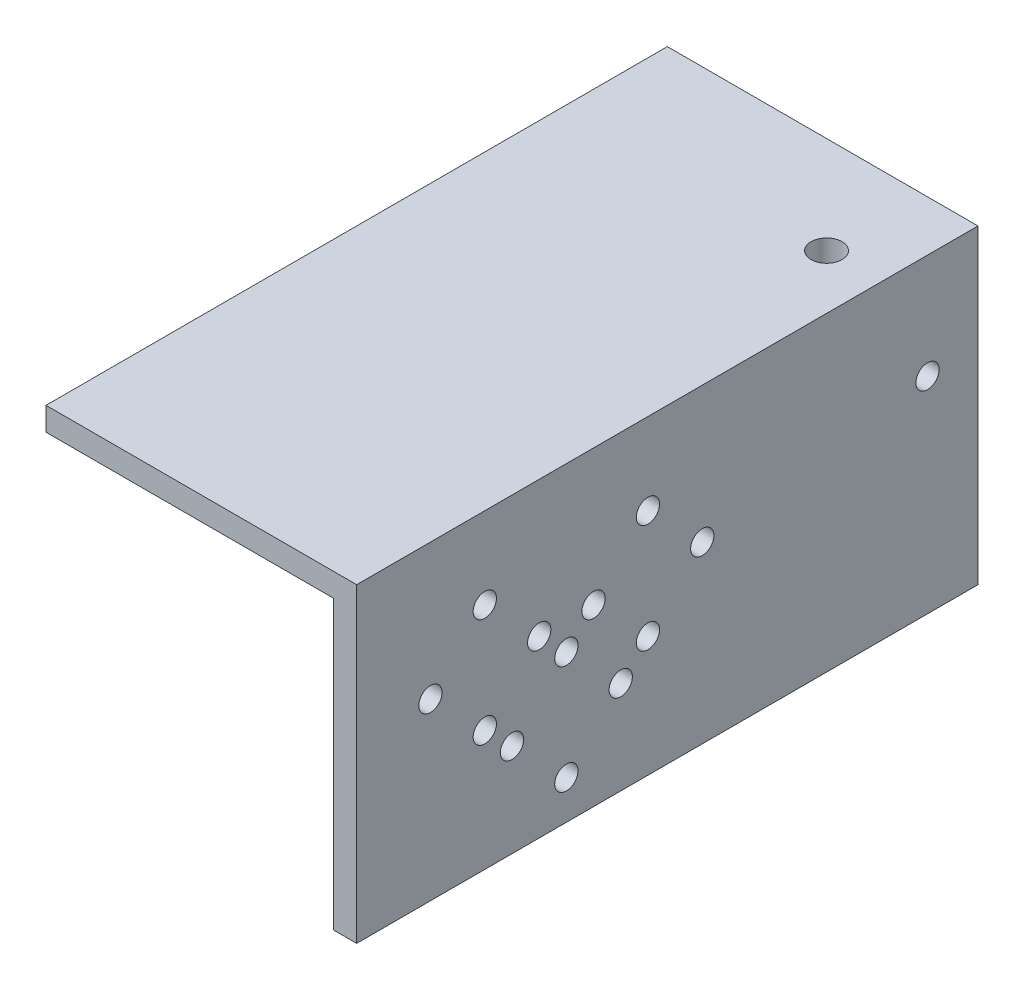
SolidWorks part; units mm, degrees
ref_plane "前视基准面" through (0, 0, 0) normal (0, 0, 1) x (1, 0, 0)
ref_plane "上视基准面" through (0, 0, 0) normal (0, 1, 0) x (1, 0, 0)
ref_plane "右视基准面" through (0, 0, 0) normal (1, 0, 0) x (0, 0, -1)
sketch "草图1" plane through (0, 0, 0) normal (0, 0, 1) x (1, 0, 0)
  line L1 (0, 0) -> (40, 0)
  line L2 (0, 0) -> (0, -40)
  line L3 (0, -40) -> (40, -40)
  line L4 (40, 0) -> (40, -40)
  dimension "D1" = 40
  dimension "D2" = 40
extrude "凸台-拉伸1" add sketch "草图1" against normal blind 80
shell "抽壳1" thickness 3
sketch "草图2" plane through (40, 0, 0) normal (1, 0, 0) x (0, 0, -1)
  line L0 (80, -40) -> (80, 0) construction
  line L1 (80, 0) -> (0, 0) construction
  line L2 (27, -35) -> (27, -21) construction
  line L3 (20, -28) -> (34, -28) construction
  line L4 (9.5, -17.5) -> (44.5, -17.5) construction
  line L5 (16.5, -10.5) -> (16.5, -24.5) construction
  line L6 (37.5, -10.5) -> (37.5, -24.5) construction
  line L7 (80, -40) -> (0, -40) construction
  circle A0 centre (44.5, -17.5) radius 1.5
  circle A1 centre (27, -21) radius 1.5
  circle A2 centre (34, -28) radius 1.5
  circle A3 centre (27, -35) radius 1.5
  circle A4 centre (20, -28) radius 1.5
  circle A5 centre (73.5, -13.5) radius 1.5
  circle A6 centre (16.5, -10.5) radius 1.5
  circle A7 centre (23.5, -17.5) radius 1.5
  circle A8 centre (9.5, -17.5) radius 1.5
  circle A9 centre (16.5, -24.5) radius 1.5
  circle A10 centre (37.5, -24.5) radius 1.5
  circle A11 centre (30.5, -17.5) radius 1.5
  circle A12 centre (37.5, -10.5) radius 1.5
  dimension "D3" = 6.5
  dimension "D4" = 3
  dimension "D5" = 3
  dimension "D6" = 3
  dimension "D7" = 3
  dimension "D9" = 3
  dimension "D1" = 12
  dimension "D2" = 22.5
  dimension "D8" = 13.5
extrude "切除-拉伸1" cut sketch "草图2" against normal through all
sketch "草图3" plane through (0, 0, 0) normal (0, 1, 0) x (1, 0, 0)
  line L0 (40, 80) -> (0, 80) construction
  line L1 (40, 80) -> (40, 0) construction
  circle A0 centre (33, 67.5) radius 2
  dimension "D2" = 4
  dimension "D1" = 12.5
  dimension "D3" = 7
extrude "切除-拉伸2" cut sketch "草图3" against normal blind 80
